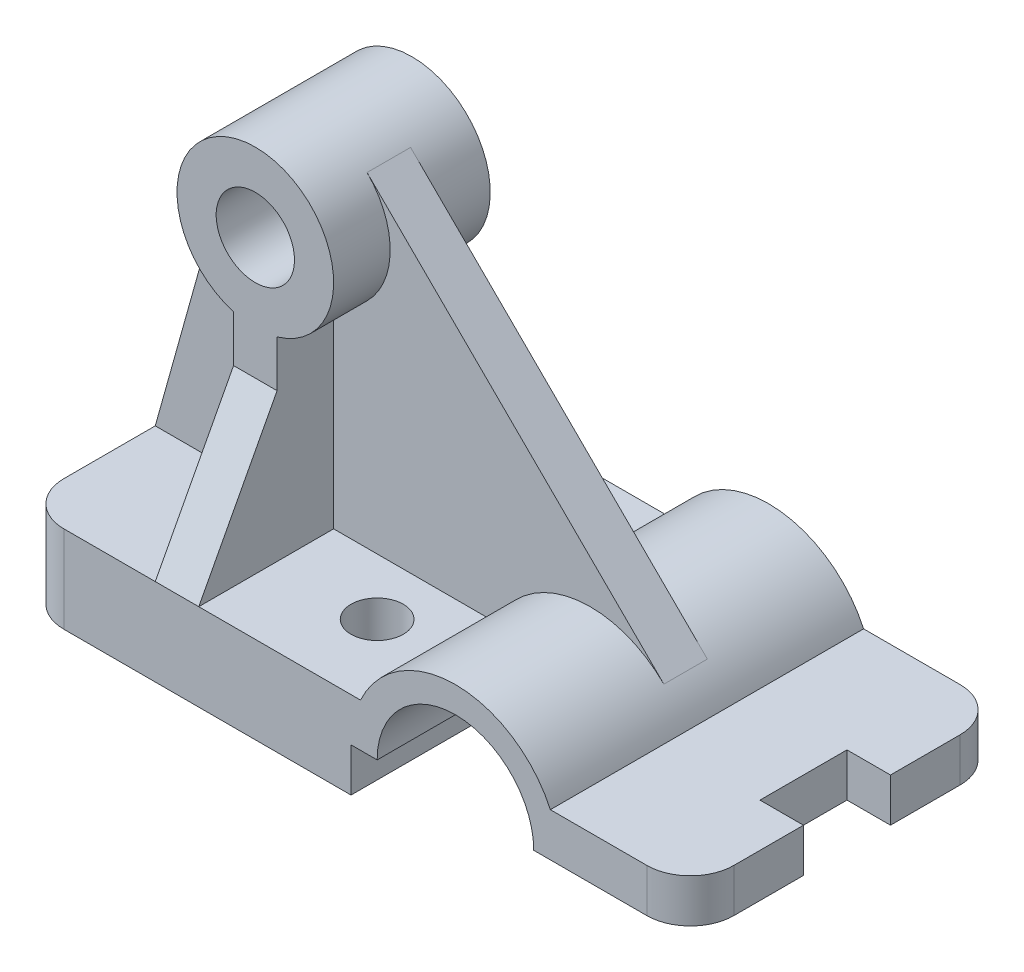
SolidWorks part; units mm, degrees
ref_plane "Front Plane" through (0, 0, 0) normal (0, 0, 1) x (1, 0, 0)
ref_plane "Top Plane" through (0, 0, 0) normal (0, 1, 0) x (1, 0, 0)
ref_plane "Right Plane" through (0, 0, 0) normal (1, 0, 0) x (0, 0, -1)
sketch "Sketch1" plane through (0, 0, 0) normal (0, 0, 1) x (1, 0, 0)
  line L0 (76, 0) -> (76, 10)
  line L1 (0, 0) -> (76, 0)
  line L2 (0, 0) -> (0, 20)
  line L3 (0, 20) -> (78.1826, 20)
  line L4 (118, 10) -> (154, 10)
  line L5 (76, 10) -> (82, 10)
  line L6 (154, 10) -> (154, 20)
  line L7 (154, 20) -> (121.8174, 20)
  arc A0 (82, 10) -> (118, 10) centre (100, 10) cw
  arc A1 (121.8174, 20) -> (78.1826, 20) centre (100, 10) ccw
  dimension "D1" = 154
  dimension "D6" = 18
  dimension "D7" = 24
  dimension "D2" = 76
  dimension "D3" = 10
  dimension "D4" = 6
  dimension "D5" = 54
  dimension "D8" = 20
extrude "Boss-Extrude1" add sketch "Sketch1" along normal blind 72
fillet "Fillet1" radius 10 4 edges at (154, 15, 0) (154, 15, 72) (0, 10, 72) (0, 10, 0)
sketch "Sketch2" plane through (0, 20, 0) normal (0, 1, 0) x (1, 0, 0)
  line L0 (154, -36) -> (121.8174, -36) construction
  line L1 (154, -62) -> (154, -10) construction
  line L2 (121.8174, -72) -> (121.8174, 0) construction
  line L4 (154, -26) -> (144, -26)
  line L5 (154, -26) -> (154, -46)
  line L6 (154, -46) -> (144, -46)
  line L7 (144, -26) -> (144, -46)
  dimension "D1" = 10
  dimension "D2" = 20
  dimension "D3" = 10
extrude "Cut-Extrude1" cut sketch "Sketch2" against normal blind 72
ref_plane "Plane1" through (0, 0, 36) normal (0, 0, 1) x (1, 0, 0)
sketch "Sketch3" plane through (0, 0, 36) normal (0, 0, 1) x (1, 0, 0)
  circle A0 centre (36, 82) radius 18
  circle A1 centre (36, 82) radius 9
  dimension "D3" = 18
  dimension "D4" = 36
  dimension "D1" = 82
  dimension "D2" = 36
extrude "Boss-Extrude2" add sketch "Sketch3" along normal mid plane 36 separate body
ref_plane "Plane2" through (36, 0, 0) normal (1, 0, 0) x (0, 0, -1)
sketch "Sketch4" plane through (36, 0, 0) normal (1, 0, 0) x (0, 0, -1)
  line L0 (-54, 54) -> (-54, 70.7108)
  line L1 (-54, 54) -> (-72, 20)
  line L2 (-54, 82) -> (-18, 82) construction
  line L3 (-54, 100) -> (-54, 64) construction
  line L4 (-18, 64) -> (-18, 100) construction
  line L5 (-18, 54) -> (-18, 70.7108)
  line L6 (-18, 54) -> (0, 20)
  line L7 (-36, 82) -> (-36, 20) construction
  line L8 (-72, 20) -> (0, 20)
  line L9 (-54, 70.7108) -> (-18, 70.7108)
  point P17 (0, 0)
  point P18 (-54, 69.1479)
  point P19 (-18, 72.1839)
  point P22 (0, 0)
  point P23 (0, 0)
  dimension "D1" = 28
  dimension "D2" = 28
  dimension "D3" = 70.7108
extrude "Boss-Extrude4" add sketch "Sketch4" along normal mid plane 10 contours L0 L9 L5 L6 L8 L1
sketch "Sketch6" plane through (0, 0, 36) normal (0, 0, 1) x (1, 0, 0)
  line L0 (48.6824, 94.7733) -> (116.9099, 27.031)
  arc A0 (41, 64.7084) -> (31, 64.7084) centre (36, 82) ccw construction
  arc A1 (121.8174, 20) -> (78.1826, 20) centre (100, 10) ccw construction
rib "Rib20" sketch "Sketch6" sketch "Sketch6" thickness 10 extrusion direction parallel to sketch draft on no parameters "D1"=10
sketch "Sketch7" plane through (0, 0, 36) normal (0, 0, 1) x (1, 0, 0)
  line L0 (0, 20) -> (18.6631, 86.8408)
  arc A0 (41, 64.7084) -> (31, 64.7084) centre (36, 82) ccw construction
rib "Rib21" sketch "Sketch7" sketch "Sketch7" thickness 10 extrusion direction parallel to sketch draft on no parameters "D1"=10
sketch "Sketch8" plane through (0, 0, 0) normal (0, 1, 0) x (1, 0, 0)
  line L1 (0, -31) -> (0, -10) construction
  line L2 (78.1826, -72) -> (41, -72) construction
  line L3 (78.1826, 0) -> (41, 0) construction
  line L4 (0, -62) -> (0, -41) construction
  circle A0 centre (64, -18) radius 6
  circle A1 centre (64, -54) radius 6
  dimension "D1" = 64
  dimension "D4" = 12
  dimension "D5" = 12
  dimension "D2" = 18
  dimension "D3" = 18
  dimension "D6" = 64
extrude "Cut-Extrude2" cut sketch "Sketch8" along normal blind 100
